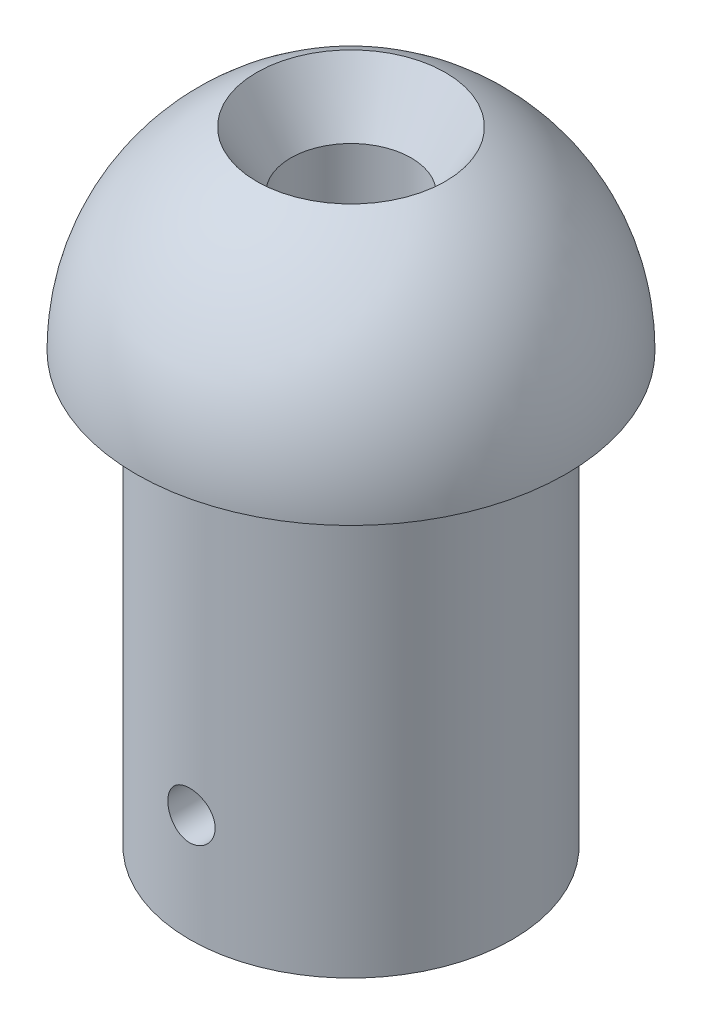
SolidWorks part; units mm, degrees
ref_plane "Front Plane" through (0, 0, 0) normal (0, 0, 1) x (1, 0, 0)
ref_plane "Top Plane" through (0, 0, 0) normal (0, 1, 0) x (1, 0, 0)
ref_plane "Right Plane" through (0, 0, 0) normal (1, 0, 0) x (0, 0, -1)
sketch "Sketch2" plane through (0, 0, 0) normal (0, 0, 1) x (1, 0, 0)
  line L0 (0, 67.5376) -> (0, -59.7187) construction
  line L1 (12.7, 0) -> (0, 0)
  line L2 (0, 0) -> (0, 12.7)
  arc A0 (12.7, 0) -> (0, 12.7) centre (0, 0) ccw
  dimension "D1" = 12.7
revolve "Revolve2" add sketch "Sketch2" angle 360 about L0
sketch "Sketch3" plane through (0, 0, 0) normal (0, -1, 0) x (1, 0, 0)
  circle A0 centre (0, 0) radius 9.525
extrude "Boss-Extrude1" add sketch "Sketch3" along normal blind 25.4
sketch "Sketch5" plane through (0, -25.4, 0) normal (0, -1, 0) x (1, 0, 0)
  circle A0 centre (0, 0) radius 3.556
extrude "Cut-Extrude1" cut sketch "Sketch5" against normal through all
ref_plane "Plane1" through (0, 12.7, 0) normal (0, 1, 0) x (1, 0, 0)
sketch "Sketch6" plane through (0, 12.7, 0) normal (0, 1, 0) x (1, 0, 0)
  circle A0 centre (0, 0) radius 6.35
extrude "Cut-Extrude2" cut sketch "Sketch6" against normal blind 5.08 draft 31
ref_plane "Plane2" through (0, 0, 12.7) normal (0, 0, 1) x (1, 0, 0)
sketch "Sketch7" plane through (0, 0, 12.7) normal (0, 0, 1) x (1, 0, 0)
  circle A0 centre (0, -19.05) radius 1.397
  dimension "D1" = 19.05
extrude "Cut-Extrude3" cut sketch "Sketch7" against normal through all contours A0
